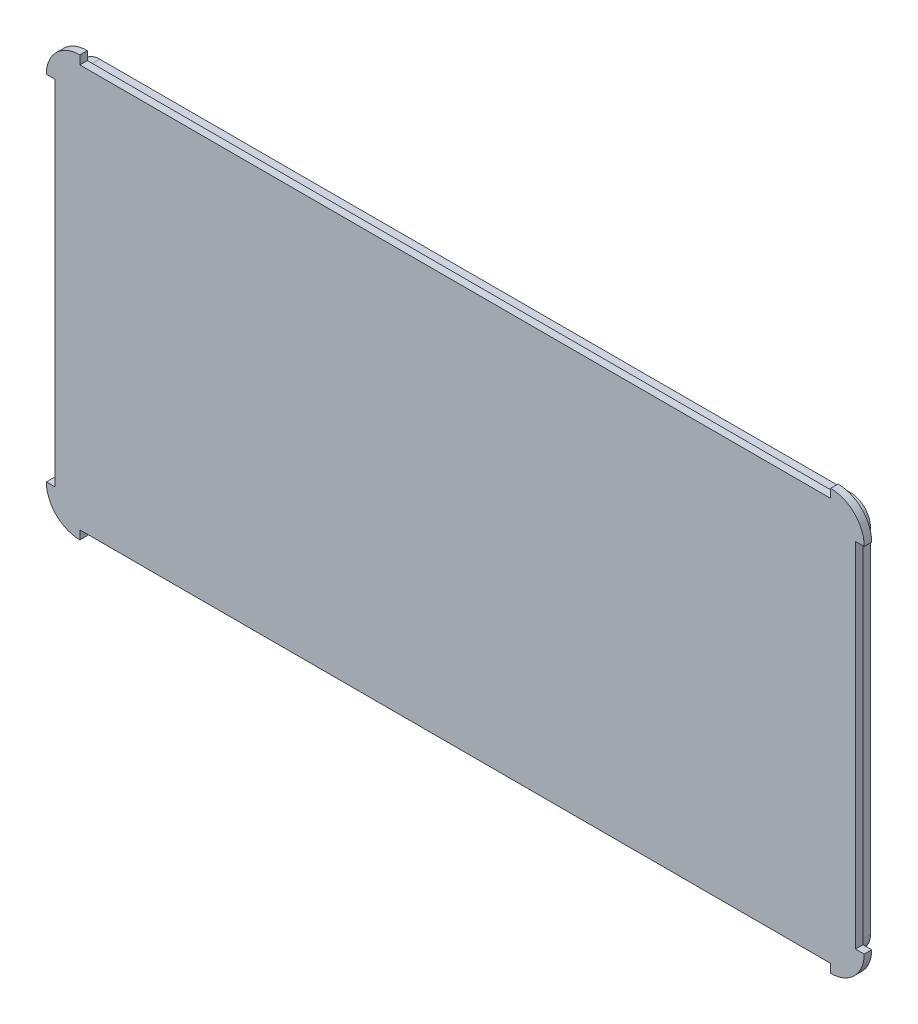
SolidWorks part; units mm, degrees
material "Стекло кварцевое прозрачное"
ref_plane "Спереди" through (0, 0, 0) normal (0, 0, 1) x (1, 0, 0)
ref_plane "Сверху" through (0, 0, 0) normal (0, 1, 0) x (1, 0, 0)
ref_plane "Справа" through (0, 0, 0) normal (1, 0, 0) x (0, 0, -1)
sketch "Sketch3" plane through (0, 0, 0) normal (0, 0, 1) x (1, 0, 0)
  line L4 (-161, 0) -> (161, 0) construction
  line L12 (0, 81) -> (0, -81) construction
  line L13 (-151, 81) -> (151, 81)
  line L14 (-161, 71) -> (-161, -71)
  line L15 (-151, -81) -> (151, -81)
  line L24 (161, 71) -> (161, -71)
  line L25 (-161, 81) -> (161, -81) construction
  line L26 (-161, -81) -> (161, 81) construction
  arc A12 (151, -81) -> (161, -71) centre (151, -71) ccw
  arc A13 (151, 81) -> (161, 71) centre (151, 71) cw
  arc A14 (-161, -71) -> (-151, -81) centre (-151, -71) ccw
  arc A15 (-151, 81) -> (-161, 71) centre (-151, 71) ccw
  point P0 (0, 0)
  dimension "D4" = 10
  dimension "D2" = 322
  dimension "D3" = 162
extrude "Boss-Extrude2" add sketch "Sketch3" against normal blind 3
sketch "Эскиз1" plane through (0, 0, -3) normal (0, 0, -1) x (-1, 0, 0)
  line L8 (-151, -79) -> (151, -79)
  line L9 (159, -71) -> (159, 71)
  line L10 (151, 79) -> (-151, 79)
  line L11 (-159, 71) -> (-159, -71)
  line L12 (-151, -79) -> (151, -79)
  line L13 (159, -71) -> (159, 71)
  line L14 (151, 79) -> (-151, 79)
  line L15 (-159, 71) -> (-159, -71)
  arc A8 (-159, -71) -> (-151, -79) centre (-151, -71) ccw
  arc A9 (151, -79) -> (159, -71) centre (151, -71) ccw
  arc A10 (159, 71) -> (151, 79) centre (151, 71) ccw
  arc A11 (-151, 79) -> (-159, 71) centre (-151, 71) ccw
  arc A12 (-159, -71) -> (-151, -79) centre (-151, -71) ccw
  arc A13 (151, -79) -> (159, -71) centre (151, -71) ccw
  arc A14 (159, 71) -> (151, 79) centre (151, 71) ccw
  arc A15 (-151, 79) -> (-159, 71) centre (-151, 71) ccw
  dimension "D1" = 2
extrude "Бобышка-Вытянуть1" add sketch "Эскиз1" along normal blind 5
sketch "Эскиз2" plane through (0, 0, 0) normal (0, 0, 1) x (1, 0, 0)
  line L2 (-164.5, 71) -> (-151, 71)
  line L3 (-151, 84.5) -> (-151, 71)
  line L5 (0, 105.4581) -> (0, -106.2128) construction
  line L6 (-173.7104, 0) -> (184.3927, 0) construction
  line L9 (164.5, -71) -> (151, -71)
  line L10 (151, -84.5) -> (151, -71)
  line L11 (-151, -84.5) -> (-151, -71)
  line L12 (-164.5, -71) -> (-151, -71)
  line L13 (151, 84.5) -> (151, 71)
  line L14 (164.5, 71) -> (151, 71)
  arc A1 (-164.5, 71) -> (-151, 84.5) centre (-151, 71) cw
  arc A3 (164.5, -71) -> (151, -84.5) centre (151, -71) cw
  arc A4 (-164.5, -71) -> (-151, -84.5) centre (-151, -71) ccw
  arc A6 (164.5, 71) -> (151, 84.5) centre (151, 71) ccw
  point P11 (0, 0)
  point P13 (0, 0)
  point P29 (0, 0)
  point P30 (167.9214, 87.9214)
extrude "Бобышка-Вытянуть2" add sketch "Эскиз2" against normal up to surface (3 mm away) contours A1 L3 L2
equation "\"длина стекла\"=321 + 1"
equation "\"ширина стекла\"=161 + 1"
equation "\"D2@Sketch3\"=\"длина стекла\""
equation "\"D3@Sketch3\"=\"ширина стекла\""
